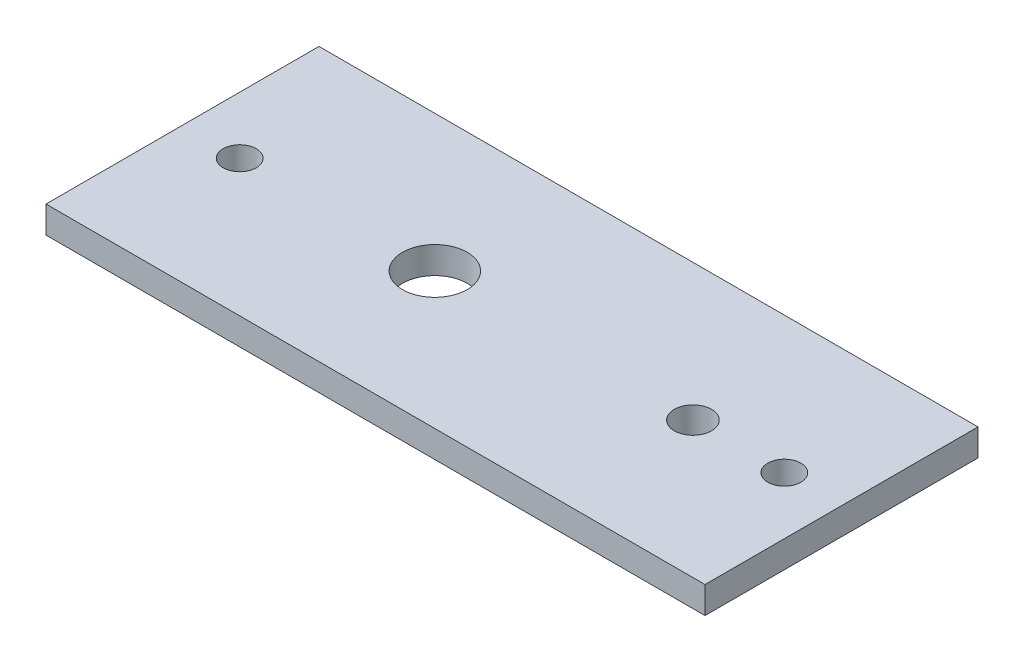
SolidWorks part; units mm, degrees
ref_plane "Front Plane" through (0, 0, 0) normal (0, 0, 1) x (1, 0, 0)
ref_plane "Top Plane" through (0, 0, 0) normal (0, 1, 0) x (1, 0, 0)
ref_plane "Right Plane" through (0, 0, 0) normal (1, 0, 0) x (0, 0, -1)
sketch "Sketch1" plane through (0, 0, 0) normal (0, 1, 0) x (1, 0, 0)
  line L0 (0, 16.7415) -> (0, -16.7415) construction
  line L1 (-40.4155, 16.7415) -> (40.4155, 16.7415)
  line L2 (-40.4155, 16.7415) -> (-40.4155, -16.7415)
  line L3 (-40.4155, -16.7415) -> (40.4155, -16.7415)
  line L4 (40.4155, 16.7415) -> (40.4155, -16.7415)
  line L5 (-40.4155, 16.7415) -> (40.4155, -16.7415) construction
  line L6 (-40.4155, -16.7415) -> (40.4155, 16.7415) construction
  circle A0 centre (-33.401, 0) radius 2.032
  circle A1 centre (33.401, 0) radius 2.032
  point P0 (0, 0)
  dimension "D1" = 4.064
  dimension "D2" = 33.401
extrude "Boss-Extrude1" add sketch "Sketch1" along normal blind 3.302
sketch "Sketch2" plane through (0, 0, 0) normal (0, -1, 0) x (1, 0, 0)
  line L1 (-40.4155, 16.7415) -> (40.4155, 16.7415) construction
  circle A0 centre (-9.4615, 0) radius 3.9687
  circle A3 centre (22.2091, 0.0162) radius 2.286
  dimension "D2" = 31.6706
  dimension "D3" = 4.572
  dimension "D4" = 7.9375
  dimension "D5" = 16.7253
extrude "Cut-Extrude1" cut sketch "Sketch2" against normal up to surface (3.302 mm away) up to face at (-33.401, 3.302, 2.032)
